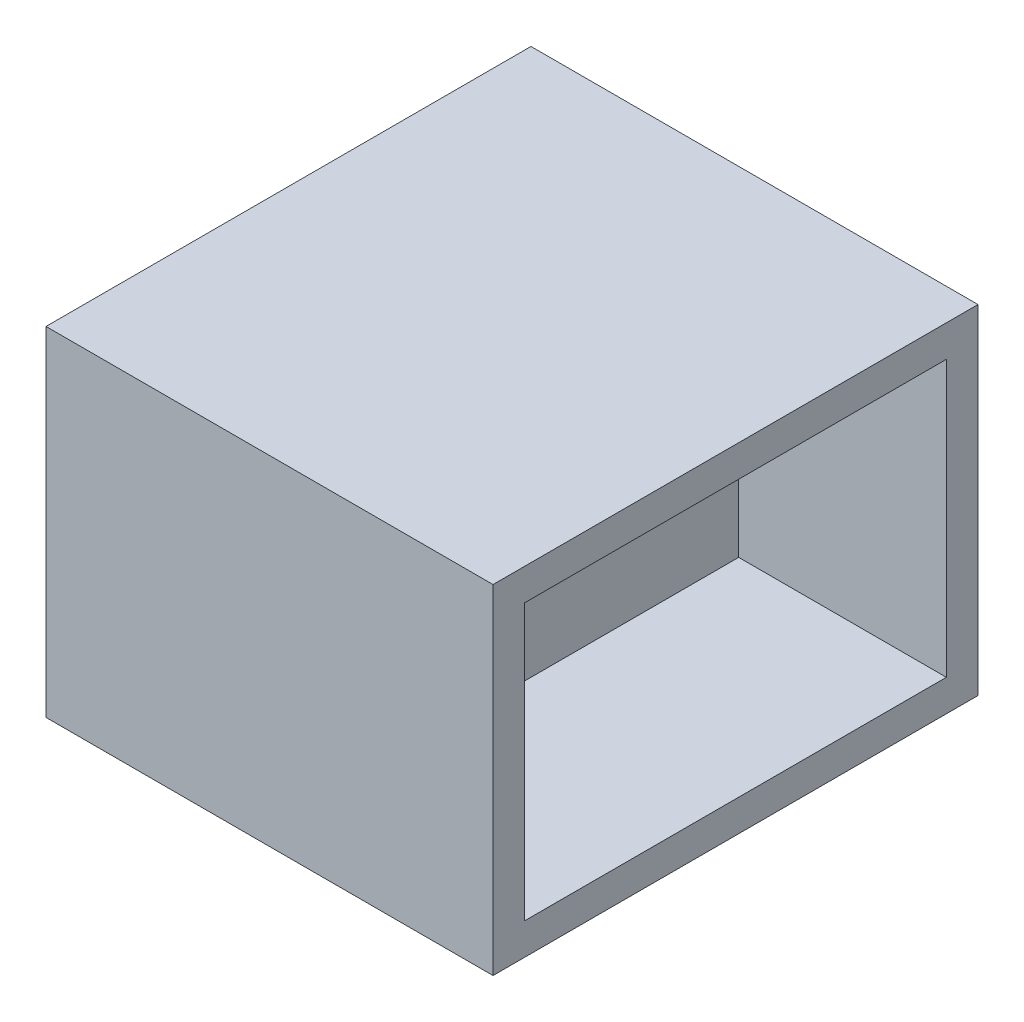
SolidWorks part; units mm, degrees
ref_plane "Front Plane" through (0, 0, 0) normal (0, 0, 1) x (1, 0, 0)
ref_plane "Top Plane" through (0, 0, 0) normal (0, 1, 0) x (1, 0, 0)
ref_plane "Right Plane" through (0, 0, 0) normal (1, 0, 0) x (0, 0, -1)
sketch "Sketch1" plane through (0, 0, 0) normal (0, 0, 1) x (1, 0, 0)
  line L1 (-21.2, -16.06) -> (21.2, -16.06)
  line L2 (-21.2, -16.06) -> (-21.2, 16.06)
  line L3 (-21.2, 16.06) -> (21.2, 16.06)
  line L4 (21.2, -16.06) -> (21.2, 16.06)
  line L5 (-21.2, -16.06) -> (21.2, 16.06) construction
  line L6 (-21.2, 16.06) -> (21.2, -16.06) construction
  point P0 (0, 0)
  dimension "D1" = 32.12
  dimension "D2" = 42.4
extrude "Boss-Extrude1" add sketch "Sketch1" along normal blind 3
sketch "Sketch2" plane through (0, 0, 3) normal (0, 0, 1) x (1, 0, 0)
  line L0 (21.2, -16.06) -> (21.2, 16.06) construction
  line L1 (-21.2, 16.06) -> (21.2, 16.06)
  line L2 (-21.2, 16.06) -> (-21.2, 13.06)
  line L3 (-21.2, 13.06) -> (21.2, 13.06)
  line L4 (21.2, 16.06) -> (21.2, 13.06)
  line L6 (-21.2, -16.06) -> (21.2, -16.06)
  line L7 (-21.2, -16.06) -> (-21.2, -13.06)
  line L8 (-21.2, -13.06) -> (21.2, -13.06)
  line L9 (21.2, -16.06) -> (21.2, -13.06)
  line L10 (-1.5, -16.06) -> (1.5, -16.06)
  line L11 (-1.5, -16.06) -> (-1.5, 16.06)
  line L12 (-1.5, 16.06) -> (1.5, 16.06)
  line L13 (1.5, -16.06) -> (1.5, 16.06)
  line L14 (-1.5, -16.06) -> (1.5, 16.06) construction
  line L15 (-1.5, 16.06) -> (1.5, -16.06) construction
  point P11 (0, 0)
  line M4 (21.2, -16.06) -> (21.2, 16.06)
  line M5 (21.2, 16.06) -> (-21.2, 16.06)
  line M6 (-21.2, 16.06) -> (-21.2, -16.06)
  dimension "D1" = 3
  dimension "D2" = 3
  dimension "D3" = 3
extrude "Boss-Extrude2" add sketch "Sketch2" along normal blind 40 contours L8 L13 L3 L11 | L3 L11 L1 M6 | L13 L3 M4 M5 | L3 L13 L1 L11
sketch "Sketch3" plane through (0, 0, 43) normal (0, 0, 1) x (1, 0, 0)
  line L1 (-21.2, -16.06) -> (21.2, -16.06)
  line L2 (-21.2, -16.06) -> (-21.2, 16.06)
  line L3 (-21.2, 16.06) -> (21.2, 16.06)
  line L4 (21.2, -16.06) -> (21.2, 16.06)
extrude "Boss-Extrude3" add sketch "Sketch3" along normal blind 3
